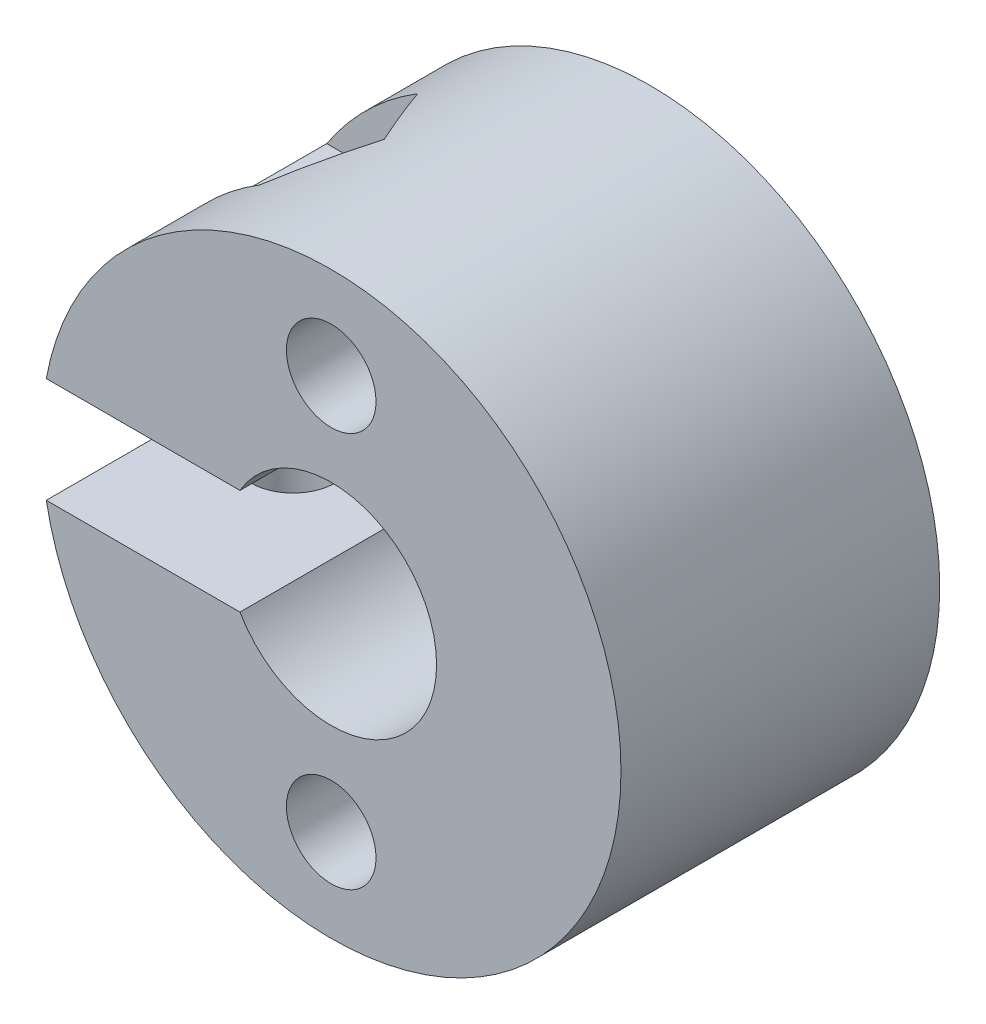
SolidWorks part; units mm, degrees
material "环氧树脂,未充填"
ref_plane "前视基准面" through (0, 0, 0) normal (0, 0, 1) x (1, 0, 0)
ref_plane "上视基准面" through (0, 0, 0) normal (0, 1, 0) x (1, 0, 0)
ref_plane "右视基准面" through (0, 0, 0) normal (1, 0, 0) x (0, 0, -1)
other "Configuration Table"
sketch "草图1" plane through (0, 0, 0) normal (0, 0, 1) x (1, 0, 0)
  line L0 (0.1658, 0) -> (50000.1658, 0) construction
  line L1 (-10.8167, 2) -> (-3.4641, 2)
  line L2 (-10.8167, -2) -> (-3.4641, -2)
  circle A0 centre (0, 0) radius 4
  circle A1 centre (0, 0) radius 11
  dimension "D1" = 8
  dimension "D2" = 22
  dimension "D3" = 4
extrude "凸台-拉伸1" add sketch "草图1" along normal mid plane 12.1 contours A0 L0 A1 L1 | L0 A0 L2 A1
sketch "草图3" plane through (0, 0, 0) normal (0, 1, 0) x (1, 0, 0)
  line L0 (0, 0) -> (-4, 0) construction
  line L1 (-4, 0) -> (-11, 0) construction
  circle A0 centre (-7.5, 0) radius 1.6
  dimension "D3" = 3.2
  dimension "D1" = 4
  dimension "D2" = 11
extrude "切除-拉伸1" cut sketch "草图3" against normal mid plane 25
sketch "草图4" plane through (0, 0, -6.05) normal (0, 0, -1) x (-1, 0, 0)
  line L0 (0, 11) -> (0, 4) construction
  line L2 (0, -4) -> (0, -11) construction
  arc A0 (10.8167, 2) -> (10.8167, -2) centre (0, 0) ccw construction
  arc A1 (3.4641, 2) -> (3.4641, -2) centre (0, 0) ccw construction
  circle A2 centre (0, 7.5) radius 1.7
  circle A3 centre (0, -7.5) radius 1.7
  dimension "D1" = 3.4
extrude "切除-拉伸2" cut sketch "草图4" against normal blind 25
ref_plane "基准面1" through (0, -6, 0) normal (0, -1, 0) x (-1, 0, 0)
sketch "草图5" plane through (0, -6, 0) normal (0, -1, 0) x (-1, 0, 0)
  circle A0 centre (7.5, 0) radius 3
  dimension "D1" = 6
extrude "切除-拉伸3" cut sketch "草图5" along normal blind 10
ref_plane "基准面2" through (0, 6, 0) normal (0, -1, 0) x (-1, 0, 0)
sketch "草图6" plane through (0, 6, 0) normal (0, -1, 0) x (-1, 0, 0)
  line L1 (10.9641, 0) -> (9.2321, 3)
  line L2 (9.2321, 3) -> (5.7679, 3)
  line L3 (5.7679, 3) -> (4.0359, 0)
  line L4 (4.0359, 0) -> (5.7679, -3)
  line L5 (5.7679, -3) -> (9.2321, -3)
  line L6 (9.2321, -3) -> (10.9641, 0)
  circle A0 centre (7.5, 0) radius 3 construction
  dimension "D1" = 6
extrude "切除-拉伸4" cut sketch "草图6" against normal blind 10
